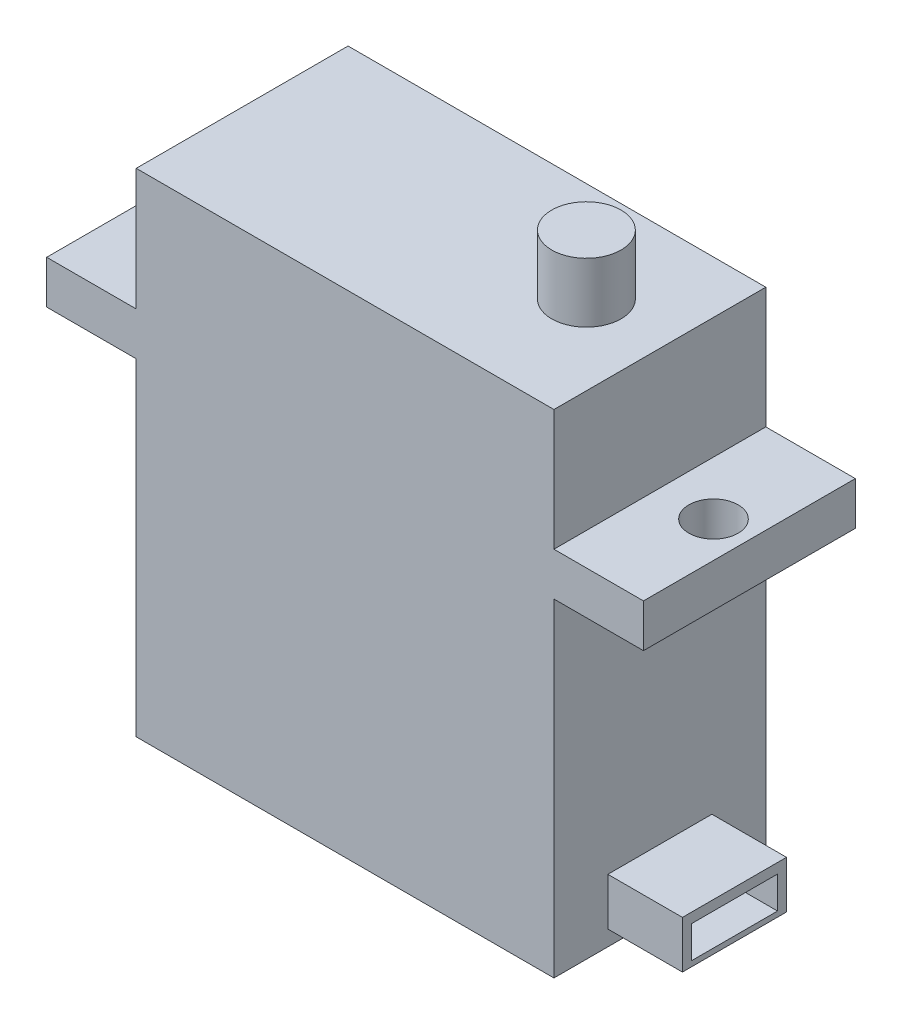
SolidWorks part; units mm, degrees
ref_plane "Front Plane" through (0, 0, 0) normal (0, 0, 1) x (1, 0, 0)
ref_plane "Top Plane" through (0, 0, 0) normal (0, 1, 0) x (1, 0, 0)
ref_plane "Right Plane" through (0, 0, 0) normal (1, 0, 0) x (0, 0, -1)
sketch "Sketch1" plane through (0, 0, 0) normal (0, 1, 0) x (1, 0, 0)
  line L1 (0, 0) -> (-28, 0)
  line L2 (0, 0) -> (0, 14.2)
  line L3 (0, 14.2) -> (-28, 14.2)
  line L4 (-28, 0) -> (-28, 14.2)
  dimension "D1" = 28
  dimension "D2" = 14.2
extrude "Boss-Extrude1" add sketch "Sketch1" along normal blind 33
sketch "Sketch2" plane through (0, 33, 0) normal (0, 1, 0) x (1, 0, 0)
  circle A0 centre (-5.3315, 7.5063) radius 2.3219
  dimension "D1" = 4.6438
extrude "Boss-Extrude3" add sketch "Sketch2" along normal blind 4
sketch "Sketch3" plane through (0, 0, 0) normal (1, 0, 0) x (0, 0, -1)
  line L1 (10.5874, 1.0363) -> (3.6126, 1.0363)
  line L2 (10.5874, 1.0363) -> (10.5874, 4.2126)
  line L3 (10.5874, 4.2126) -> (3.6126, 4.2126)
  line L4 (3.6126, 1.0363) -> (3.6126, 4.2126)
  line L5 (10.5874, 1.0363) -> (3.6126, 4.2126) construction
  line L6 (10.5874, 4.2126) -> (3.6126, 1.0363) construction
  point P0 (7.1, 2.6245)
  dimension "D1" = 24.485
  dimension "D2" = 6.9748
  dimension "D3" = 3.1763
  dimension "D4" = 6.9748
extrude "Boss-Extrude4" add sketch "Sketch3" along normal blind 5
sketch "Sketch4" plane through (5, 0, 0) normal (1, 0, 0) x (0, 0, -1)
  line L5 (4.2112, 1.393) -> (9.9888, 1.393)
  line L6 (4.2112, 1.393) -> (4.2112, 3.5428)
  line L7 (4.2112, 3.5428) -> (9.9888, 3.5428)
  line L8 (9.9888, 1.393) -> (9.9888, 3.5428)
  line L9 (4.2112, 1.393) -> (9.9888, 3.5428) construction
  line L10 (4.2112, 3.5428) -> (9.9888, 1.393) construction
  point P0 (7.1, 2.4679)
extrude "Cut-Extrude1" cut sketch "Sketch4" against normal blind 5
ref_plane "Plane1" through (-28, 0, 0) normal (0, 1, 0) x (1, 0, 0)
sketch "Sketch6" plane through (-28, 0, 0) normal (-1, 0, 0) x (0, 0, 1)
  line L0 (0, 0) -> (0, 21.9439)
  line L1 (0, 33) -> (0, 0) construction
  line L2 (0, 21.9439) -> (-14.2, 21.9439)
  line L3 (-14.2, 33) -> (-14.2, 0) construction
  line L5 (-14.2, 21.9439) -> (0, 21.9439)
  line L6 (-14.2, 21.9439) -> (-14.2, 24.8367)
  line L7 (-14.2, 24.8367) -> (0, 24.8367)
  line L8 (0, 21.9439) -> (0, 24.8367)
  line M3 (0, 0) -> (0, 33)
  line M5 (-14.2, 33) -> (-14.2, 0)
  dimension "D1" = 14.2
extrude "Boss-Extrude5" add sketch "Sketch6" along normal blind 6 contours L7 L2 M5 M3
sketch "Sketch11" plane through (0, 0, 0) normal (1, 0, 0) x (0, 0, -1)
  line L1 (0, 33) -> (0, 0) construction
  line L2 (14.2, 33) -> (14.2, 0) construction
  line L3 (0, 22) -> (14.2, 22)
  line L4 (0, 22) -> (0, 24.89)
  line L5 (0, 24.89) -> (14.2, 24.89)
  line L6 (14.2, 22) -> (14.2, 24.89)
extrude "Boss-Extrude6" add sketch "Sketch11" along normal blind 6 contours L4 L3 L6 L5
sketch "Sketch12" plane through (0, 24.89, 0) normal (0, 1, 0) x (1, 0, 0)
  circle A0 centre (3.5945, 7.1) radius 1.651
  dimension "D1" = 3.302
extrude "Cut-Extrude4" cut sketch "Sketch12" against normal blind 6
sketch "Sketch17" plane through (0, 24.8367, 0) normal (0, 1, 0) x (1, 0, 0)
  circle A0 centre (-31.3352, 7.1) radius 1.651
  dimension "D1" = 3.302
extrude "Cut-Extrude5" cut sketch "Sketch17" against normal through all
